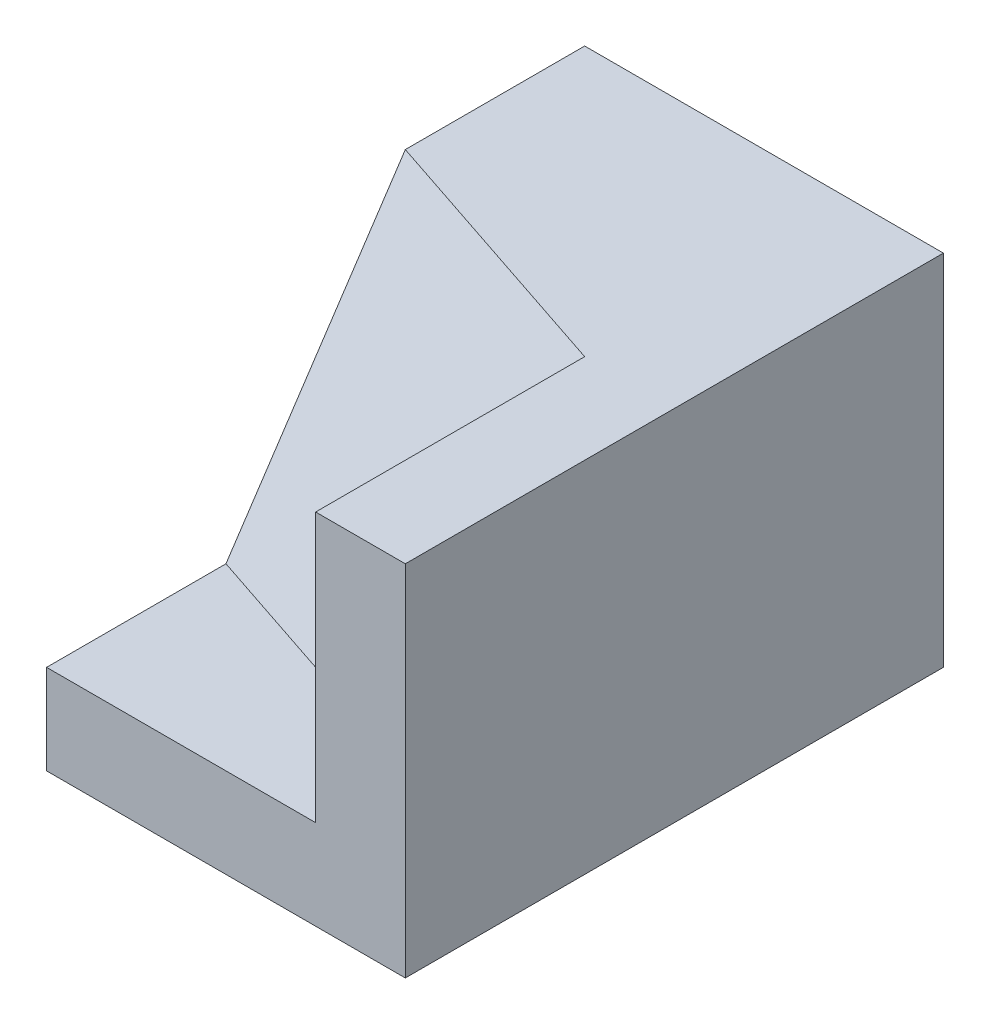
SolidWorks part; units mm, degrees
ref_plane "前基準面" through (0, 0, 0) normal (0, 0, 1) x (1, 0, 0)
ref_plane "上基準面" through (0, 0, 0) normal (0, 1, 0) x (1, 0, 0)
ref_plane "右基準面" through (0, 0, 0) normal (1, 0, 0) x (0, 0, -1)
sketch "草圖10" plane through (0, 0, 0) normal (1, 0, 0) x (0, 0, -1)
  line L1 (-32.8767, -4.3562) -> (27.1233, -4.3562)
  line L2 (-32.8767, -4.3562) -> (-32.8767, 35.6438)
  line L3 (-32.8767, 35.6438) -> (27.1233, 35.6438)
  line L4 (27.1233, -4.3562) -> (27.1233, 35.6438)
  dimension "D1" = 60
  dimension "D2" = 40
extrude "填料-伸長3" add sketch "草圖10" along normal blind 40
sketch "草圖11" plane through (0, 35.6438, 0) normal (0, 1, 0) x (1, 0, 0)
  line L0 (0, -12.8767) -> (30, -22.8767)
  line L1 (0, 27.1233) -> (0, -32.8767) construction
  line L2 (30, -22.8767) -> (30, -32.8767)
  line L3 (40, -32.8767) -> (0, -32.8767) construction
  line L4 (0, -12.8767) -> (0, -32.8767)
  line L5 (0, -32.8767) -> (30, -32.8767)
  dimension "D1" = 10
  dimension "D2" = 30
  dimension "D3" = 20
extrude "除料-伸長2" cut sketch "草圖11" against normal blind 30
sketch "草圖12" plane through (30, 0, 0) normal (-1, 0, 0) x (0, 0, 1)
  line L0 (22.8767, 5.6438) -> (2.8767, 35.6438)
  line L1 (12.8767, 5.6438) -> (32.8767, 5.6438) construction
  line L2 (-27.1233, 35.6438) -> (12.8767, 35.6438) construction
  line L3 (2.8767, 35.6438) -> (32.8767, 35.6438)
  line L4 (32.8767, 35.6438) -> (32.8767, 5.6438)
  line L5 (32.8767, 5.6438) -> (22.8767, 5.6438)
  dimension "D1" = 30
sketch "草圖13" plane through (0, 5.6438, 0) normal (0, 1, 0) x (1, 0, 0)
  line L0 (30, -22.8767) -> (0, -12.8767)
  line L1 (0, 27.1233) -> (0, -12.8767) construction
  line L2 (0, -32.8767) -> (30, -32.8767) construction
  dimension "D1" = 20
sweep "除料-掃出1" cut profiles "草圖12" path "草圖13"
